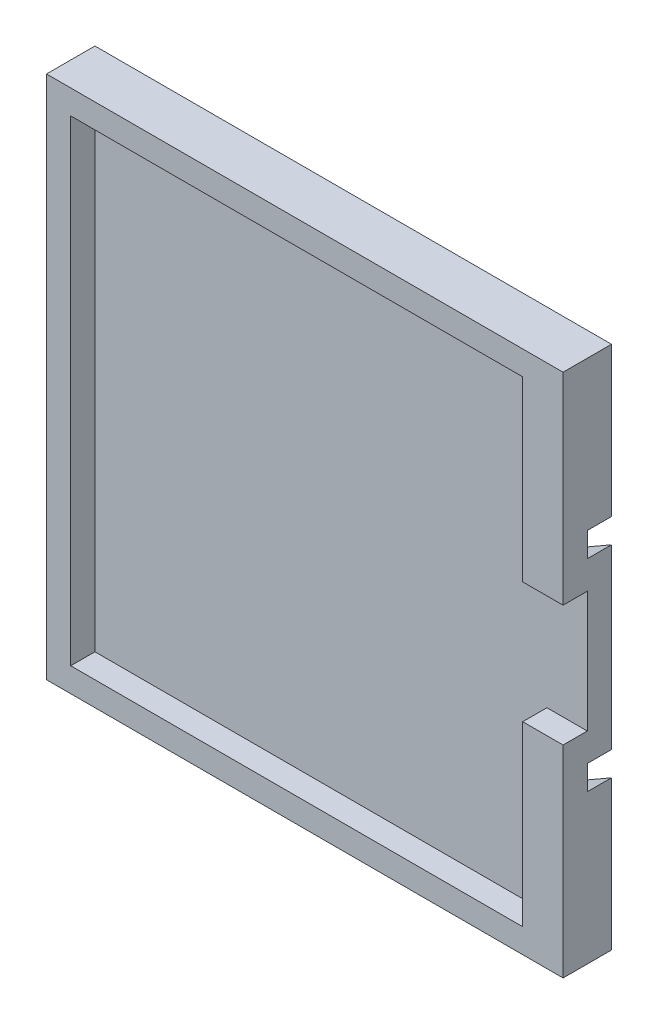
SolidWorks part; units mm, degrees
ref_plane "Front Plane" through (0, 0, 0) normal (0, 0, 1) x (1, 0, 0)
ref_plane "Top Plane" through (0, 0, 0) normal (0, 1, 0) x (1, 0, 0)
ref_plane "Right Plane" through (0, 0, 0) normal (1, 0, 0) x (0, 0, -1)
sketch "Sketch1" plane through (0, 0, 0) normal (0, 0, 1) x (1, 0, 0)
  line L0 (0, 0) -> (-40751.263, 0) construction
  line L1 (-64, -65) -> (64, -65)
  line L2 (-64, -65) -> (-64, 65)
  line L3 (-64, 65) -> (64, 65)
  line L4 (64, -65) -> (64, -28.0278)
  line L7 (15, 17) -> (49, 17)
  line L8 (15, 17) -> (15, -17)
  line L9 (15, -17) -> (49, -17)
  line L10 (49, 17) -> (49, -17)
  line L11 (0, 0) -> (0, 40751.263) construction
  line L20 (15, -23) -> (15, -57)
  line L21 (15, -23) -> (49, -23)
  line L22 (49, -23) -> (49, -57)
  line L23 (15, -57) -> (49, -57)
  line L24 (15, -118.7352) -> (15, -152.7352) [skipped]
  line L25 (15, -118.7352) -> (49, -118.7352) [skipped]
  line L26 (49, -118.7352) -> (49, -152.7352) [skipped]
  line L27 (15, -152.7352) -> (49, -152.7352) [skipped]
  line L28 (15, -158.7352) -> (15, -192.7352) [skipped]
  line L29 (15, -158.7352) -> (49, -158.7352) [skipped]
  line L30 (49, -158.7352) -> (49, -192.7352) [skipped]
  line L31 (15, -192.7352) -> (49, -192.7352) [skipped]
  line L32 (15, 57) -> (15, 23)
  line L33 (15, 57) -> (49, 57)
  line L34 (49, 57) -> (49, 23)
  line L35 (15, 23) -> (49, 23)
  line L52 (64, 21.9722) -> (64, -21.9722)
  line L53 (64, -22.1188) -> (56, -17.5) construction
  line L54 (56, -17.5) -> (56, -32.5) construction
  line L55 (56, -32.5) -> (64, -27.8812) construction
  line L60 (64, -21.9722) -> (64, 21.9722)
  line L61 (64, 28.0278) -> (64, 65)
  line L62 (64.0635, -22.0088) -> (55.873, -17.28) construction
  line L63 (55.873, -32.72) -> (64.0635, -27.9912) construction
  line L64 (55.873, 32.72) -> (64, 28.0278)
  line L65 (64, -21.9722) -> (55.873, -17.28)
  line L66 (55.873, -17.28) -> (55.873, -32.72)
  line L67 (55.873, -32.72) -> (64, -28.0278)
  line L68 (64, 21.9722) -> (55.873, 17.28)
  line L69 (55.873, 17.28) -> (55.873, 32.72)
  line L70 (64, -22.1188) -> (64, -27.8812) construction
  point P0 (0, 0)
  point P14 (15, 0)
  point P15 (0, -65)
  point P62 (55.873, -25)
  dimension "D1" = 34
  dimension "D2" = 34
  dimension "D3" = 15
  dimension "D6" = 8
  dimension "D7" = 15
  dimension "D8" = 6
  dimension "D10" = 6
  dimension "D11" = 8
  dimension "D12" = 60
  dimension "D13" = 60
  dimension "D14" = 8.127
  dimension "D15" = 15.4399
  dimension "D16" = 8
  dimension "D19" = 25
  dimension "D4" = 2
  dimension "D5" = 2
  dimension "D9" = 2
extrude "Boss-Extrude1" add sketch "Sketch1" along normal blind 6 contours L68 L69 L64 L61 L3 L2 L1 L4 L67 L66 L65 L52 L7 L10 L9 L8 L23 L20 L21 L22 L35 L32 L33 L34 | L10 L7 L8 L9 | L32 L35 L34 L33 | L20 L23 L22 L21
sketch "Sketch2" plane through (0, 0, 6) normal (0, 0, 1) x (1, 0, 0)
  line L1 (-64, 65) -> (64, 65)
  line L2 (-64, 65) -> (-64, -65)
  line L3 (-64, -65) -> (64, -65)
  line L4 (64, 65) -> (64, 15)
  line L8 (0, 0) -> (115.6244, 0) construction
  line L9 (54, 15) -> (64, 15)
  line L10 (54, -15) -> (64, -15)
  line L12 (54, 59) -> (54, 15)
  line L13 (64, -15) -> (64, -65)
  line L17 (54, -15) -> (54, -59)
  line L18 (-54, -55) -> (54, -55) construction
  line L19 (-54, 55) -> (54, 55) construction
  line L20 (-54, 55) -> (-54, -55) construction
  line L21 (-58, -59) -> (54, -59)
  line L22 (-58, 59) -> (-58, -59)
  line L23 (-58, 59) -> (54, 59)
  line L24 (54, 55) -> (54, 15) construction
  line L25 (54, -15) -> (54, -55) construction
  line L26 (-58, -59) -> (64, -59) construction
  line L27 (-58, 59) -> (64, 59) construction
  dimension "D2" = 15
  dimension "D1" = 10
  dimension "D3" = 6
extrude "Boss-Extrude2" add sketch "Sketch2" along normal blind 6
